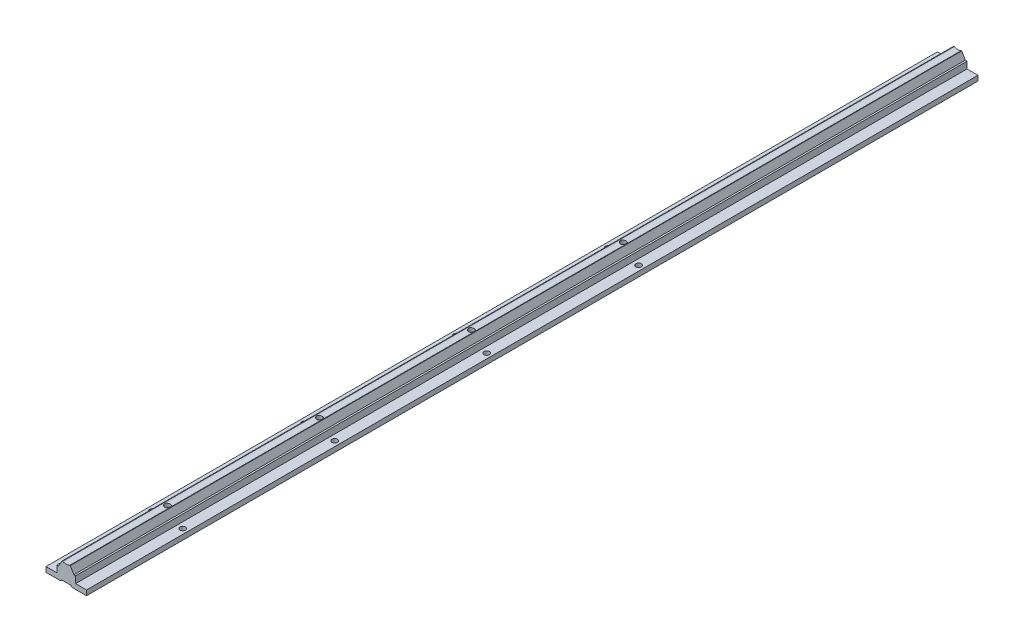
SolidWorks part; units mm, degrees
material "6063-T5"
ref_plane "Front Plane" through (0, 0, 0) normal (0, 0, 1) x (1, 0, 0)
ref_plane "Top Plane" through (0, 0, 0) normal (0, 1, 0) x (1, 0, 0)
ref_plane "Right Plane" through (0, 0, 0) normal (1, 0, 0) x (0, 0, -1)
sketch "Sketch1" plane through (0, 0, 0) normal (0, 0, 1) x (1, 0, 0)
  line L0 (-20, -25) -> (-5.4717, -25)
  line L1 (-5.4717, -25) -> (-4.75, -23.75)
  line L2 (-4.75, -23.75) -> (4.75, -23.75)
  line L3 (4.75, -23.75) -> (5.4717, -25)
  line L4 (5.4717, -25) -> (20, -25)
  line L5 (20, -25) -> (20, -20)
  line L6 (20, -20) -> (9.25, -20)
  line L7 (9.25, -20) -> (9.25, -13.3)
  line L8 (9.25, -13.3) -> (7.5218, -13.3)
  line L9 (-3.4871, -7.2) -> (-4, -7.2)
  line L10 (-20, -25) -> (-20, -20)
  line L11 (-20, -20) -> (-9.25, -20)
  line L12 (-9.25, -20) -> (-9.25, -13.3)
  line L13 (-9.25, -13.3) -> (-7.5218, -13.3)
  line L14 (3.4871, -7.2) -> (4, -7.2)
  line L15 (-7.5218, -13.3) -> (-4, -7.2)
  line L16 (0, -8) -> (0, 0) construction
  line L17 (4, -7.2) -> (7.5218, -13.3)
  line L18 (0, -8) -> (0, -23.75) construction
  arc A0 (-3.4871, -7.2) -> (3.4871, -7.2) centre (0, 0) ccw
  dimension "D1" = 8
  dimension "D2" = 17.8
  dimension "D3" = 5
  dimension "D4" = 25
  dimension "D5" = 11.7
  dimension "D6" = 18.5
  dimension "D7" = 20
  dimension "D8" = 8
  dimension "D9" = 60
  dimension "D10" = 9.5
  dimension "D11" = 60
  dimension "D12" = 1.25
  dimension "D13" = 40
extrude "Length" add sketch "Sketch1" along normal blind 880
sketch "Sketch2" plane through (0, -25, 0) normal (0, -1, 0) x (1, 0, 0)
  line L0 (-20, 880) -> (-20, 0) construction
  line L1 (-20, 880) -> (-5.4717, 880) construction
  circle A0 centre (-15, 780) radius 2.75
  circle A1 centre (15, 780) radius 2.75
  dimension "D2" = 5.5
  dimension "D1" = 5
  dimension "D3" = 30
  dimension "D4" = 100
extrude "Cut-Extrude1" cut sketch "Sketch2" against normal up to next
hole_wizard "CBORE for M5 Hex Head Bolt1" positions "Sketch4" profile "Sketch5" counterbore size "M5" standard "Ansi Metric" end condition through all
sketch "Sketch4" plane through (0, -23.75, 0) normal (0, -1, 0) x (1, 0, 0)
  line L0 (20, 880) -> (20, 0) construction
  line L1 (-4.75, 880) -> (4.75, 880) construction
  point P0 (0, 780)
  point P4 (0, 880)
  dimension "D1" = 20
  dimension "D2" = 100
sketch "Sketch5" plane through (0, -23.75, 780) normal (1, 0, 0) x (0, 0, -1)
  line L0 (0, 0) -> (0, 16.55)
  line L1 (0, 16.55) -> (2.75, 16.55)
  line L3 (2.75, 16.55) -> (2.75, 3.58)
  line L4 (2.75, 3.58) -> (4.75, 3.58)
  line L5 (4.75, 3.58) -> (4.75, 0)
  line L7 (4.75, 0) -> (0, 0)
  line L11 (0, -6.35) -> (0, 107.95) construction
  dimension "Thru Hole Dia." = 5.5
  dimension "Thru Hole Depth" = 16.55
  dimension "C'Bore Dia." = 9.5
  dimension "C'Bore Depth" = 3.58
pattern_linear "LPattern1" count 4 spacing 150 along (0, 0, -1) of "Cut-Extrude1"
pattern_linear "LPattern2" count 4 spacing 150 along (0, 0, -1) of "CBORE for M5 Hex Head Bolt1"
